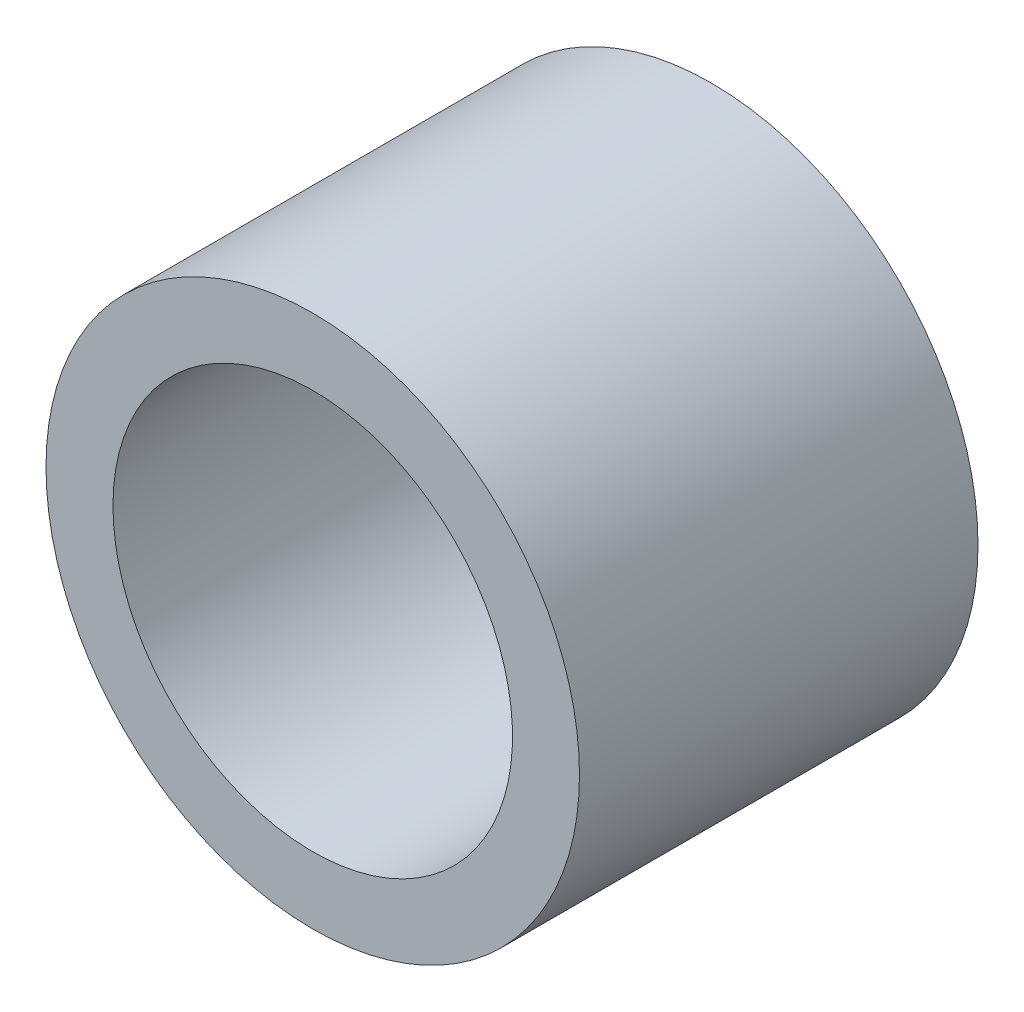
SolidWorks part; units mm, degrees
ref_plane "Front Plane" through (0, 0, 0) normal (0, 0, 1) x (1, 0, 0)
ref_plane "Top Plane" through (0, 0, 0) normal (0, 1, 0) x (1, 0, 0)
ref_plane "Right Plane" through (0, 0, 0) normal (1, 0, 0) x (0, 0, -1)
sketch "Sketch1" plane through (0, 0, 0) normal (0, 0, 1) x (1, 0, 0)
  circle A0 centre (0, 0) radius 6.3754
  circle A1 centre (0, 0) radius 4.7752
  dimension "D1" = 12.7508
  dimension "ID" = 9.5504
extrude "Extrude1" add sketch "Sketch1" along normal mid plane 9.525
sketch "Sketch2" plane through (0, 0, 0) normal (1, 0, 0) x (0, 0, -1)
  line L0 (-4.7625, -4.7752) -> (4.7625, -4.7752) construction
  line L3 (4.7625, 4.7752) -> (-4.7625, 4.7752) construction
  line L5 (-4.7625, -4.7752) -> (4.7625, -4.7752)
  line L6 (4.7625, 4.7752) -> (-4.7625, 4.7752)
sketch "Sketch4" plane through (0, 0, 4.7625) normal (0, 0, 1) x (1, 0, 0)
  line L0 (0, 0) -> (-3.3766, 3.3766)
  line L1 (0, -3.4925) -> (0, 3.4925) construction
  circle A0 centre (0, 0) radius 4.7752 construction
  dimension "D1" = 45
